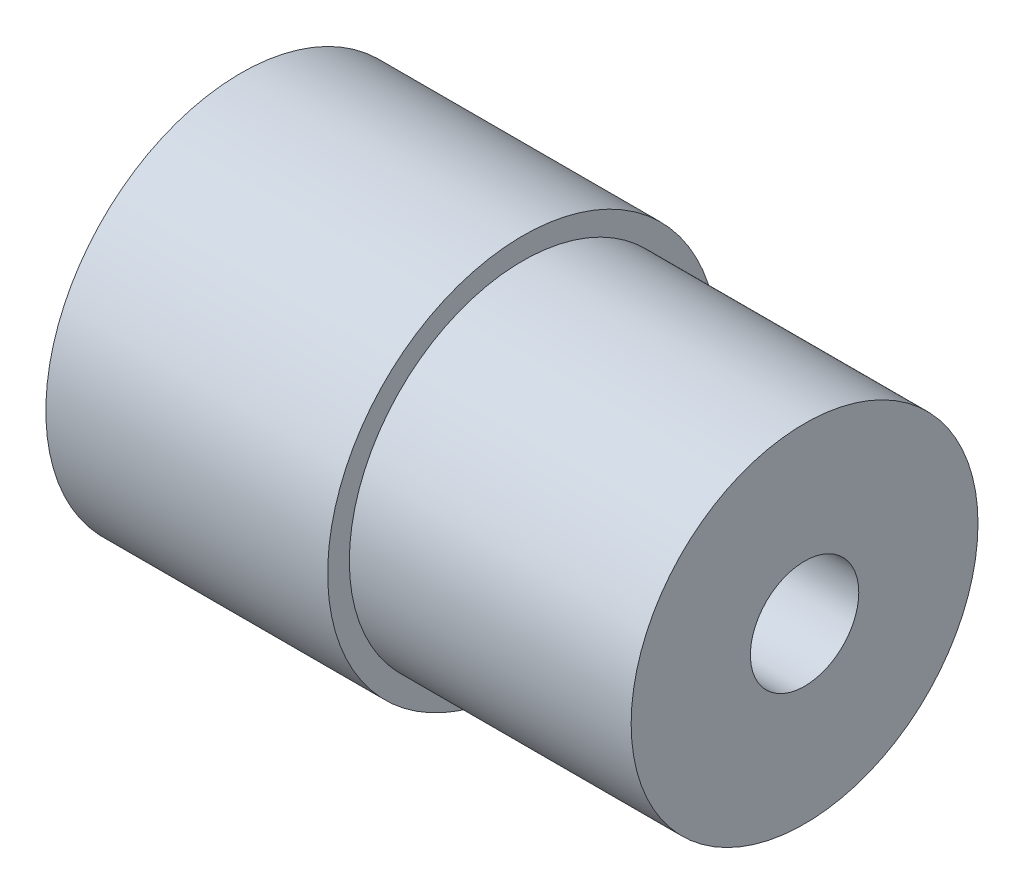
SolidWorks part; units mm, degrees
ref_plane "Front Plane" through (0, 0, 0) normal (0, 0, 1) x (1, 0, 0)
ref_plane "Top Plane" through (0, 0, 0) normal (0, 1, 0) x (1, 0, 0)
ref_plane "Right Plane" through (0, 0, 0) normal (1, 0, 0) x (0, 0, -1)
sketch "Esquisse1" plane through (0, 0, 0) normal (0, 0, 1) x (1, 0, 0)
  line L0 (0, 0) -> (-149.7826, 0) construction
  line L1 (0, 0) -> (0, 8)
  line L2 (0, 8) -> (-13, 8)
  line L3 (-13, 8) -> (-13, 9)
  line L4 (-13, 9) -> (-26, 9)
  line L5 (-26, 9) -> (-26, 0)
  line L6 (-26, 0) -> (0, 0)
  dimension "D1" = 8
  dimension "D2" = 13
  dimension "D3" = 1
  dimension "D4" = 13
revolve "Révolution1" add sketch "Esquisse1" angle 360 about L0
sketch "Esquisse2" plane through (0, 0, 0) normal (1, 0, 0) x (0, 0, -1)
  circle A0 centre (0, 0) radius 2.5
  dimension "D1" = 5
extrude "Enlèv. mat.-Extru.1" cut sketch "Esquisse2" against normal through all
sketch "Esquisse3" plane through (-26, 0, 0) normal (-1, 0, 0) x (0, 0, 1)
  circle A0 centre (0, 0) radius 4
  dimension "D1" = 8
extrude "Enlèv. mat.-Extru.2" cut sketch "Esquisse3" against normal offset from surface (8 mm away) 5 up to face at (-13, 0, -9)
sketch "Esquisse4" plane through (0, 0, 0) normal (0, 1, 0) x (1, 0, 0)
  line L0 (-13, 9) -> (-26, 9) construction
  line L1 (0, 8) -> (-13, 8) construction
  line L2 (0, -8) -> (0, 8) construction
  circle A0 centre (-20, 0) radius 1.5
  circle A1 centre (-6, 0) radius 1.5
  dimension "D1" = 3
  dimension "D2" = 3
  dimension "D3" = 9
  dimension "D4" = 8
  dimension "D5" = 6
  dimension "D6" = 6
extrude "Enlèv. mat.-Extru.3" cut sketch "Esquisse4" against normal through all
